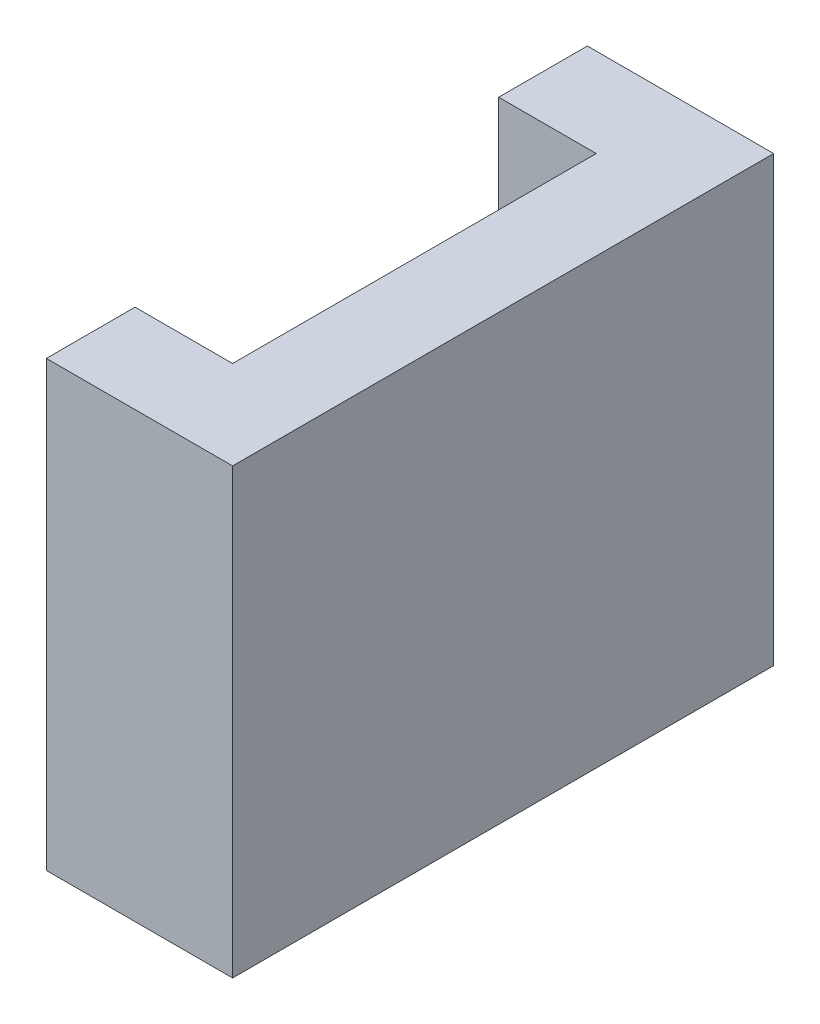
SolidWorks part; units mm, degrees
ref_plane "Front Plane" through (0, 0, 0) normal (0, 0, 1) x (1, 0, 0)
ref_plane "Top Plane" through (0, 0, 0) normal (0, 1, 0) x (1, 0, 0)
ref_plane "Right Plane" through (0, 0, 0) normal (1, 0, 0) x (0, 0, -1)
sketch "Sketch1" plane through (0, 0, 0) normal (1, 0, 0) x (0, 0, -1)
  line L1 (-14.8454, 13.1413) -> (5.6546, 13.1413)
  line L2 (-14.8454, 13.1413) -> (-14.8454, -6.8587)
  line L3 (-14.8454, -6.8587) -> (5.6546, -6.8587)
  line L4 (5.6546, 13.1413) -> (5.6546, -6.8587)
  line L5 (-19.8454, 13.1413) -> (10.6546, 13.1413)
  line L6 (-19.8454, 13.1413) -> (-19.8454, -11.8587)
  line L7 (-19.8454, -11.8587) -> (10.6546, -11.8587)
  line L8 (10.6546, 13.1413) -> (10.6546, -11.8587)
  dimension "D1" = 20
  dimension "D2" = 20.5
  dimension "D3" = 5
  dimension "D4" = 5
  dimension "D5" = 5
extrude "Boss-Extrude1" add sketch "Sketch1" along normal blind 5.5 contours L8 L5 L4 L3 L2 L6 L7
sketch "Sketch2" plane through (5.5, 0, 0) normal (1, 0, 0) x (0, 0, -1)
  line L6 (-19.8454, 13.1413) -> (10.6546, 13.1413)
  line L7 (-19.8454, 13.1413) -> (-19.8454, -11.8587)
  line L8 (-19.8454, -11.8587) -> (10.6546, -11.8587)
  line L9 (10.6546, 13.1413) -> (10.6546, -11.8587)
extrude "Boss-Extrude2" add sketch "Sketch2" along normal blind 5
